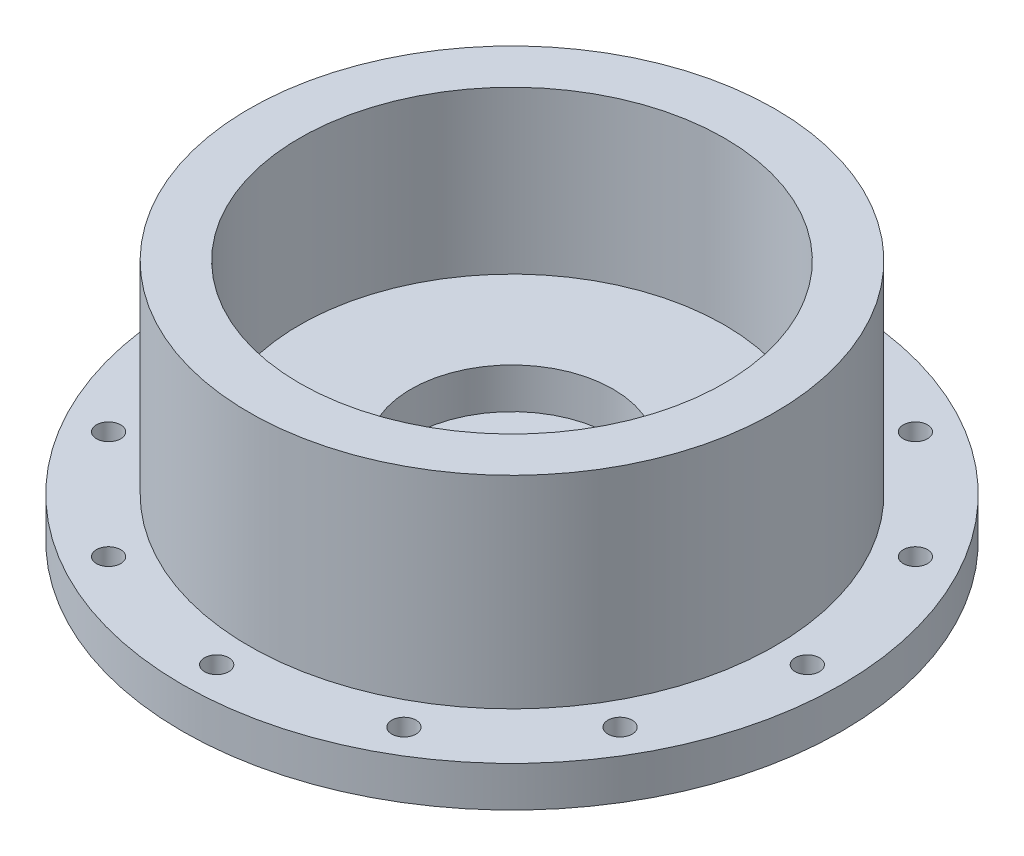
SolidWorks part; units mm, degrees
ref_plane "Front Plane" through (0, 0, 0) normal (0, 0, 1) x (1, 0, 0)
ref_plane "Top Plane" through (0, 0, 0) normal (0, 1, 0) x (1, 0, 0)
ref_plane "Right Plane" through (0, 0, 0) normal (1, 0, 0) x (0, 0, -1)
sketch "Sketch1" plane through (0, 0, 0) normal (1, 0, 0) x (0, 0, -1)
  line L0 (0, 0) -> (25, 0) construction
  line L1 (25, 0) -> (25, -10)
  line L2 (25, 0) -> (52.5, 0)
  line L3 (52.5, 0) -> (52.5, 40)
  line L4 (52.5, 40) -> (65, 40)
  line L5 (65, 40) -> (65, -10)
  line L6 (65, -10) -> (25, -10) construction
  line L7 (0, 0) -> (0, 10) construction
  line L8 (25, -10) -> (0, -10)
  line L9 (0, -10) -> (0, -20)
  line L10 (0, -20) -> (65, -20)
  line L11 (65, -20) -> (65, -10)
  dimension "D1" = 25
  dimension "D2" = 10
  dimension "D3" = 52.5
  dimension "D4" = 40
  dimension "D5" = 10
  dimension "D6" = 40
  dimension "D7" = 10
revolve "Revolve1" add sketch "Sketch1" angle 360 about L7
sketch "Sketch2" plane through (0, 0, 0) normal (0, 1, 0) x (1, 0, 0)
  line L3 (0, 0) -> (0, 73) construction
  circle A4 centre (0, 73) radius 3
  circle A8 centre (0, 0) radius 81.5
  circle A9 centre (36.5, 63.2199) radius 3
  circle A10 centre (63.2199, 36.5) radius 3
  circle A11 centre (73, 0) radius 3
  circle A12 centre (63.2199, -36.5) radius 3
  circle A13 centre (36.5, -63.2199) radius 3
  circle A14 centre (0, -73) radius 3
  circle A15 centre (-36.5, -63.2199) radius 3
  circle A16 centre (-63.2199, -36.5) radius 3
  circle A17 centre (-73, 0) radius 3
  circle A18 centre (-63.2199, 36.5) radius 3
  circle A19 centre (-36.5, 63.2199) radius 3
  point P29 (0, 0)
  dimension "D1" = 6
  dimension "D2" = 163
  dimension "D3" = 73
  dimension "D4" = 12
extrude "Boss-Extrude1" add sketch "Sketch2" along normal blind 10 from surface at -20 starting at face at (0, -20, -65)
